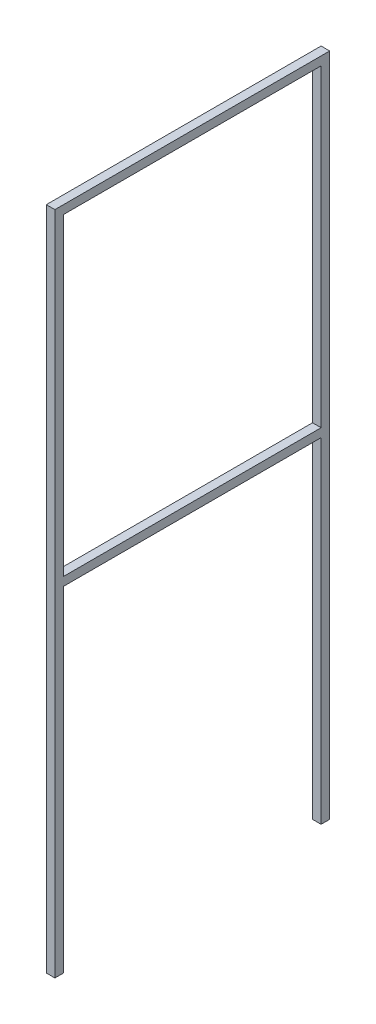
SolidWorks part; units mm, degrees
material "Plain Carbon Steel"
ref_plane "Front" through (0, 0, 0) normal (0, 0, 1) x (1, 0, 0)
ref_plane "Top" through (0, 0, 0) normal (0, 1, 0) x (1, 0, 0)
ref_plane "Right" through (0, 0, 0) normal (1, 0, 0) x (0, 0, -1)
sketch "Sketch1" plane through (0, 0, 0) normal (1, 0, 0) x (0, 0, -1)
  line L0 (0, 0) -> (0, -500)
  line L1 (0, -500) -> (-600, -500)
  line L2 (-600, -520) -> (-600, -650)
  line L3 (0, -520) -> (0, -650)
  line L4 (-600, -500) -> (-600, 0)
  line L5 (-600, -650) -> (-600, -670)
  line L6 (20, 0) -> (20, -500)
  line L7 (0, -520) -> (-600, -520)
  line L8 (-620, -500) -> (-620, 0)
  line L9 (20, -500) -> (20, -1300)
  line L10 (-620, -500) -> (-620, -1300)
  line L11 (0, -650) -> (0, -670)
  line L12 (-600, 230) -> (0, 230)
  line L13 (-600, 250) -> (0, 250)
  line L14 (20, -1300) -> (0, -1300)
  line L15 (-600, -1300) -> (-620, -1300)
  line L16 (0, -500) -> (0, -1300) construction
  line L17 (0, -670) -> (0, -1300)
  line L18 (-600, -670) -> (-600, -1300)
  line L19 (-600, -500) -> (-600, -1300) construction
  line L20 (20, 0) -> (20, 250)
  line L21 (0, 0) -> (0, 230)
  line L22 (-600, 230) -> (-600, 0)
  line L23 (-620, 250) -> (-620, 0)
  line L24 (-620, 250) -> (-600, 250)
  line L25 (0, 250) -> (20, 250)
  dimension "D1" = 500
  dimension "D2" = 800
  dimension "D3" = 20
  dimension "D5" = 20
  dimension "D6" = 20
extrude "Boss-Extrude1" add sketch "Sketch1" along normal blind 20
